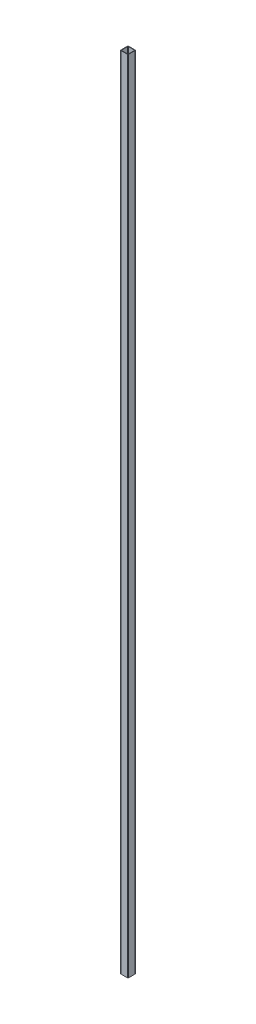
SolidWorks part; units mm, degrees
ref_plane "Спереди" through (0, 0, 0) normal (0, 0, 1) x (1, 0, 0)
ref_plane "Сверху" through (0, 0, 0) normal (0, 1, 0) x (1, 0, 0)
ref_plane "Справа" through (0, 0, 0) normal (1, 0, 0) x (0, 0, -1)
sketch "Эскиз1" plane through (0, 0, 0) normal (0, 1, 0) x (1, 0, 0)
  line L1 (18, 20) -> (-18, 20)
  line L2 (20, 18) -> (20, -18)
  line L3 (18, -20) -> (-18, -20)
  line L4 (-20, 18) -> (-20, -18)
  line L5 (20, 20) -> (-20, -20) construction
  line L6 (20, -20) -> (-20, 20) construction
  line L7 (16, 18) -> (-16, 18)
  line L8 (18, 16) -> (18, -16)
  line L9 (16, -18) -> (-16, -18)
  line L10 (-18, 16) -> (-18, -16)
  line L11 (18, 18) -> (-18, -18) construction
  line L12 (18, -18) -> (-18, 18) construction
  arc A0 (20, -18) -> (18, -20) centre (18, -18) cw
  arc A1 (18, -16) -> (16, -18) centre (16, -16) cw
  arc A2 (-16, -18) -> (-18, -16) centre (-16, -16) cw
  arc A3 (-18, -20) -> (-20, -18) centre (-18, -18) cw
  arc A4 (18, 20) -> (20, 18) centre (18, 18) cw
  arc A5 (16, 18) -> (18, 16) centre (16, 16) cw
  arc A6 (-16, 18) -> (-18, 16) centre (-16, 16) ccw
  arc A7 (-18, 20) -> (-20, 18) centre (-18, 18) ccw
  point P0 (0, 0)
  point P6 (0, 0)
  dimension "D5" = 2
  dimension "D1" = 40
  dimension "D2" = 40
  dimension "D3" = 2
  dimension "D4" = 2
extrude "Бобышка-Вытянуть1" add sketch "Эскиз1" along normal blind 4240
